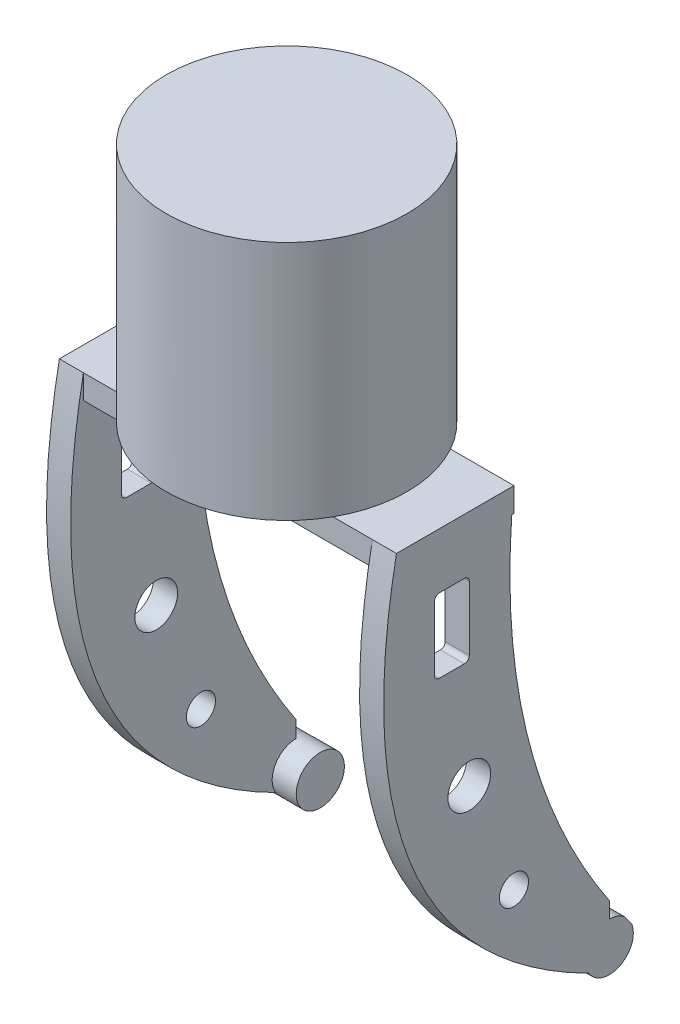
SolidWorks part; units mm, degrees
ref_plane "Front Plane" through (0, 0, 0) normal (0, 0, 1) x (1, 0, 0)
ref_plane "Top Plane" through (0, 0, 0) normal (0, 1, 0) x (1, 0, 0)
ref_plane "Right Plane" through (0, 0, 0) normal (1, 0, 0) x (0, 0, -1)
sketch "Sketch1" plane through (0, 0, 0) normal (1, 0, 0) x (0, 0, -1)
  line L0 (0, 0) -> (0, 47.171) construction
  line L1 (-22.4452, 47.171) -> (-10.0544, 47.171)
  line L3 (-17.9234, 41.31) -> (-15.2744, 41.31)
  line L4 (-18.4314, 40.802) -> (-18.4314, 34.018)
  line L5 (-17.9234, 33.51) -> (-15.2744, 33.51)
  line L6 (-14.7664, 40.802) -> (-14.7664, 34.018)
  arc A0 (-2.1728, -1.3154) -> (0, 2.54) centre (0, 0) ccw
  circle A1 centre (-14.7664, 22.0989) radius 2.2536
  circle A2 centre (-10.0544, 10.2544) radius 1.5359
  arc A3 (-18.4314, 34.018) -> (-17.9234, 33.51) centre (-17.9234, 34.018) ccw
  arc A4 (-14.7664, 34.018) -> (-15.2744, 33.51) centre (-15.2744, 34.018) cw
  arc A5 (-14.7664, 40.802) -> (-15.2744, 41.31) centre (-15.2744, 40.802) ccw
  arc A6 (-17.9234, 41.31) -> (-18.4314, 40.802) centre (-17.9234, 40.802) ccw
  spline S0 degree 2 poles (-2.1728, -1.3154) (-29.205, 12.2965) (-22.4452, 47.171) knots 0 0 0 1 1 1
  spline S1 degree 2 poles (2.3471, 0.9708) (-12.8223, 20.8478) (-10.0544, 47.171) knots 0 0 0 1 1 1
  dimension "D1" = 0.508
extrude "Boss-Extrude1" add sketch "Sketch1" along normal blind 2.54
sketch "Sketch2" plane through (0, 0, 0) normal (-1, 0, 0) x (0, 0, 1)
  circle A0 centre (0, 0) radius 2.54
extrude "Boss-Extrude2" add sketch "Sketch2" along normal blind 2.54
ref_plane "Plane1" through (-15.24, 0, 0) normal (-1, 0, 0) x (0, 0, 1)
mirror "Mirror2" about plane through (-15.24, 0, 0) normal (-1, 0, 0) of bodies 102
sketch "Sketch3" plane through (0, 47.171, 0) normal (0, 1, 0) x (1, 0, 0)
  line L1 (-33.02, -22.4452) -> (2.54, -22.4452)
  line L2 (-33.02, -22.4452) -> (-33.02, -10.0544)
  line L3 (-33.02, -10.0544) -> (2.54, -10.0544)
  line L4 (2.54, -22.4452) -> (2.54, -10.0544)
extrude "Boss-Extrude3" add sketch "Sketch3" against normal blind 2.54
sketch "Sketch4" plane through (0, 47.171, 0) normal (0, 1, 0) x (1, 0, 0)
  circle A0 centre (-15.24, -16.2498) radius 12.7
extrude "Boss-Extrude4" add sketch "Sketch4" along normal blind 25.4
